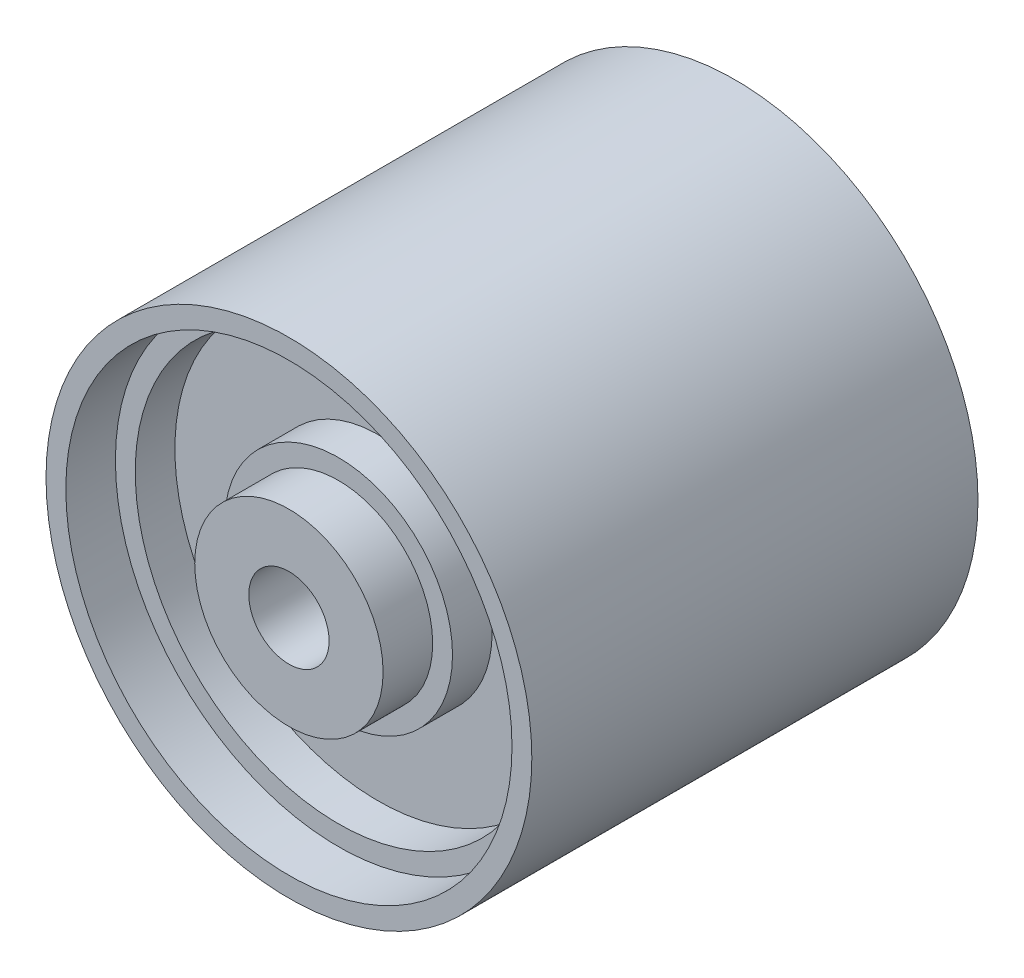
SolidWorks part; units mm, degrees
ref_plane "Front Plane" through (0, 0, 0) normal (0, 0, 1) x (1, 0, 0)
ref_plane "Top Plane" through (0, 0, 0) normal (0, 1, 0) x (1, 0, 0)
ref_plane "Right Plane" through (0, 0, 0) normal (1, 0, 0) x (0, 0, -1)
sketch "Sketch1" plane through (0, 0, 0) normal (0, 0, 1) x (1, 0, 0)
  circle A0 centre (0, 0) radius 24.5
  circle A1 centre (0, 0) radius 4.05
  dimension "D1" = 49
  dimension "D2" = 8.1
extrude "Boss-Extrude1" add sketch "Sketch1" against normal blind 45
sketch "Sketch2" plane through (0, 0, 0) normal (0, 0, 1) x (1, 0, 0)
  circle A0 centre (0, 0) radius 20.5
  circle A1 centre (0, 0) radius 11.5
  dimension "D1" = 41
  dimension "D2" = 23
extrude "Cut-Extrude1" cut sketch "Sketch2" against normal blind 9
sketch "Sketch3" plane through (0, 0, -45) normal (0, 0, -1) x (-1, 0, 0)
  circle A0 centre (0, 0) radius 20.5
  circle A1 centre (0, 0) radius 11.5
  dimension "D1" = 41
  dimension "D2" = 23
extrude "Cut-Extrude2" cut sketch "Sketch3" against normal blind 9
sketch "Sketch5" plane through (0, 0, 0) normal (0, 0, 1) x (1, 0, 0)
  circle A0 centre (0, 0) radius 22.5
  circle A1 centre (0, 0) radius 9.5
  dimension "D1" = 45
  dimension "D2" = 13
extrude "Cut-Extrude3" cut sketch "Sketch5" against normal blind 5
sketch "Sketch6" plane through (0, 0, -45) normal (0, 0, -1) x (-1, 0, 0)
  circle A0 centre (0, 0) radius 22.5
  circle A1 centre (0, 0) radius 9.5
  dimension "D1" = 45
  dimension "D2" = 13
extrude "Cut-Extrude4" cut sketch "Sketch6" against normal blind 5
